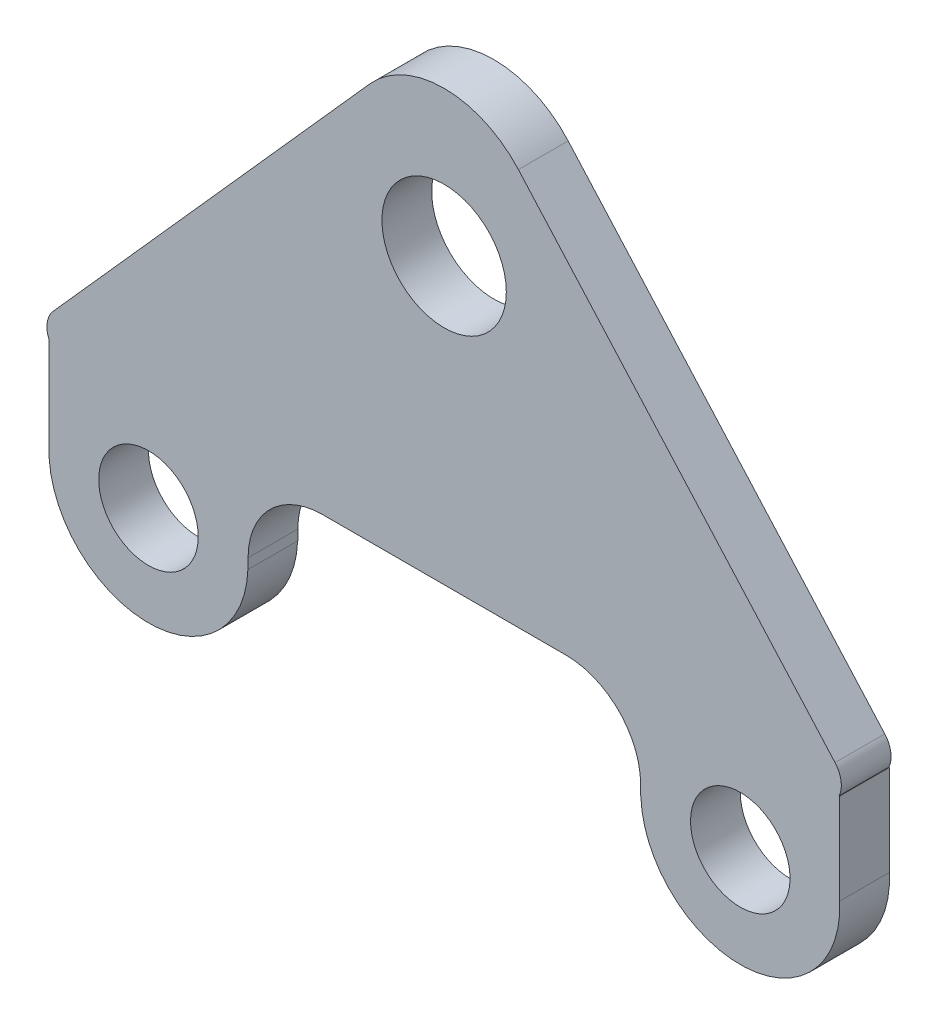
SolidWorks part; units mm, degrees
material "Silicon Rubber"
ref_plane "Front" through (0, 0, 0) normal (0, 0, 1) x (1, 0, 0)
ref_plane "Top" through (0, 0, 0) normal (0, 1, 0) x (1, 0, 0)
ref_plane "Right" through (0, 0, 0) normal (1, 0, 0) x (0, 0, -1)
sketch "Sketch2" plane through (0, 0, 0) normal (0, 0, 1) x (1, 0, 0)
  line L0 (-24.7183, 0) -> (44.0798, 0)
  line L1 (-24.7183, 0) -> (9.6807, 38.594)
  line L2 (9.6807, 38.594) -> (44.0798, 0)
  dimension "D1" = 51.6991
  dimension "D2" = 68.7981
extrude "Boss-Extrude1" add sketch "Sketch2" along normal blind 4
fillet "Fillet1" radius 8 1 edges at (9.6807, 38.594, 2)
fillet "Fillet2" radius 2 2 edges at (-24.7183, 0, 2) (44.0798, 0, 2)
sketch "Sketch3" plane through (0, 0, 0) normal (0, 0, 1) x (1, 0, 0)
  line L0 (-22.0816, 1.1819) -> (-6.0816, 1.1819)
  line L1 (-6.0816, 1.1819) -> (-6.0816, -6.8181)
  line L2 (-6.0816, -6.8181) -> (-22.0816, -6.8181)
  line L3 (-22.0816, -6.8181) -> (-22.0816, 1.1819)
  arc A0 (-21.7496, 3.3307) -> (-20.2566, 0) centre (-20.2566, 2) ccw construction
  dimension "D1" = 16
  dimension "D2" = 8
sketch "Sketch8" plane through (0, 0, 4) normal (0, 0, 1) x (1, 0, 0)
  circle A0 centre (9.6807, 22.8874) radius 5
extrude "Cut-Extrude1" cut sketch "Sketch8" against normal blind 4
extrude "Boss-Extrude2" add sketch "Sketch3" along normal blind 4
sketch "Sketch10" plane through (0, 0, 4) normal (0, 0, 1) x (1, 0, 0)
  circle A0 centre (-14.0923, -6.5484) radius 8
extrude "Boss-Extrude3" add sketch "Sketch10" against normal blind 4
fillet "Fillet3" radius 6 1 edges at (-6.0816, 0, 2)
sketch "Sketch11" plane through (0, 0, 4) normal (0, 0, 1) x (1, 0, 0)
  circle A0 centre (-14.0923, -6.5484) radius 4
extrude "Cut-Extrude2" cut sketch "Sketch11" against normal blind 4
ref_plane "Plane1" through (9.7, 0, 0) normal (1, 0, 0) x (0, 0, -1)
mirror "Mirror1" about plane through (9.7, 0, 0) normal (1, 0, 0) of "Fillet3", "Boss-Extrude3", "Boss-Extrude2", "Cut-Extrude2"
